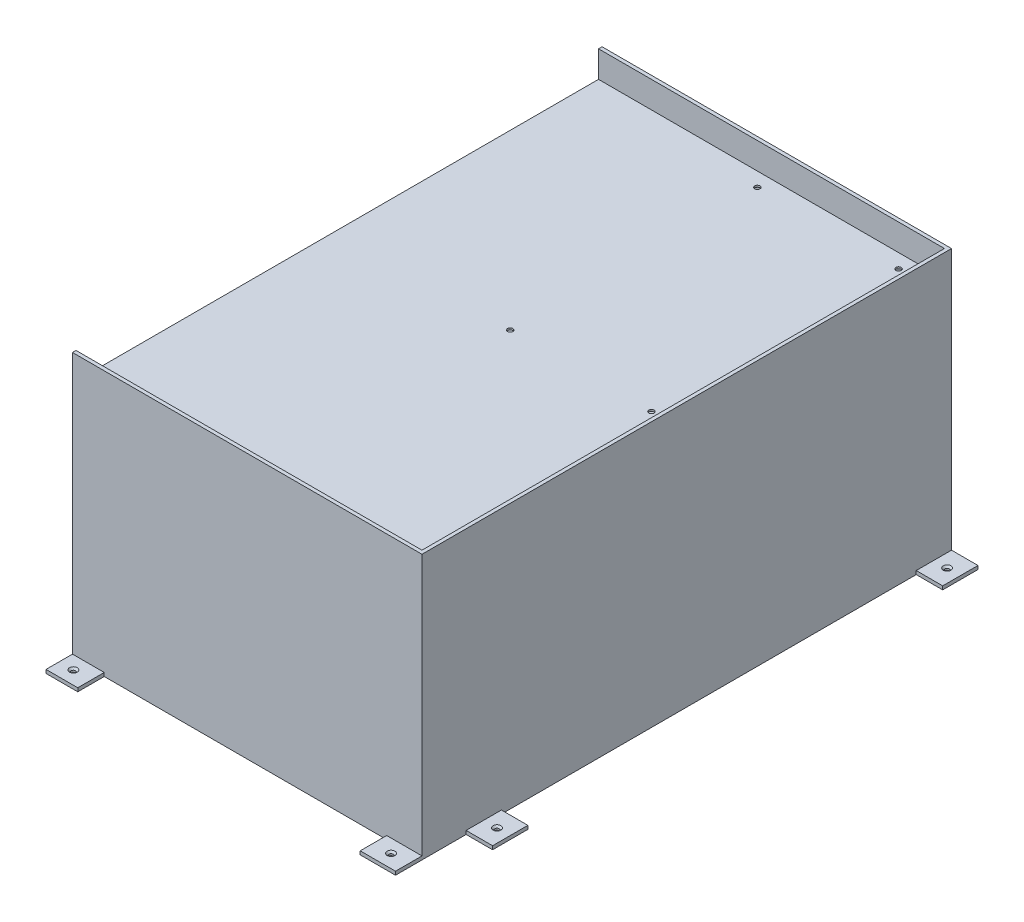
SolidWorks part; units mm, degrees
ref_plane "Front Plane" through (0, 0, 0) normal (0, 0, 1) x (1, 0, 0)
ref_plane "Top Plane" through (0, 0, 0) normal (0, 1, 0) x (1, 0, 0)
ref_plane "Right Plane" through (0, 0, 0) normal (1, 0, 0) x (0, 0, -1)
sketch "Sketch2" plane through (0, 0, 0) normal (0, 1, 0) x (1, 0, 0)
  line L1 (100, -150) -> (-100, -150)
  line L2 (100, -150) -> (100, 150)
  line L3 (100, 150) -> (-100, 150)
  line L4 (-100, -150) -> (-100, 150)
  line L5 (100, -150) -> (-100, 150) construction
  line L6 (100, 150) -> (-100, -150) construction
  point P0 (0, 0)
  dimension "D1" = 300
  dimension "D2" = 200
extrude "Boss-Extrude1" add sketch "Sketch2" along normal blind 150
shell "Shell1" thickness 2
sketch "Sketch4" plane through (0, 0, 0) normal (0, 1, 0) x (1, 0, 0)
  line L0 (-100, -150) -> (100, -150) construction
  line L5 (-100, -150) -> (-80, -150)
  line L6 (-100, -150) -> (-100, -165)
  line L7 (-100, -165) -> (-80, -165)
  line L8 (-80, -150) -> (-80, -165)
  line L9 (100, -150) -> (100, 150) construction
  line L10 (100, -150) -> (80, -150)
  line L11 (100, -150) -> (100, -165)
  line L12 (100, -165) -> (80, -165)
  line L13 (80, -150) -> (80, -165)
  line L14 (100, 150) -> (115, 150)
  line L15 (100, 150) -> (100, 130)
  line L16 (100, 130) -> (115, 130)
  line L17 (115, 150) -> (115, 130)
  line L18 (100, -125) -> (115, -125)
  line L19 (100, -125) -> (100, -105)
  line L20 (100, -105) -> (115, -105)
  line L21 (115, -125) -> (115, -105)
  dimension "D1" = 20
  dimension "D2" = 15
  dimension "D3" = 15
  dimension "D4" = 20
  dimension "D5" = 20
  dimension "D6" = 15
  dimension "D7" = 20
  dimension "D8" = 15
  dimension "D9" = 25
extrude "Boss-Extrude2" add sketch "Sketch4" along normal blind 2
hole_wizard "CSK for M2 Countersunk Flat Head Screw1" positions "3DSketch2" profile "Sketch5" countersink size "M2" standard "ISO"
sketch3d "3DSketch2"
  line L0 (-100, 2, 157.5) -> (100, 2, 157.5) construction
  line L1 (-100, 2, 150) -> (-100, 2, 165) construction
  line L2 (100, 2, 165) -> (100, 2, 150) construction
  point P0 (107.5, 2, -140)
  point P2 (107.5, 2, 115)
  point P4 (90, 2, 157.5)
  point P6 (-90, 2, 157.5)
sketch "Sketch5" plane through (107.5, 2, -140) normal (1, 0, 0) x (0, 0, 1)
  line L0 (0, 0) -> (0, 30.721)
  line L1 (0, 30.721) -> (1.2, 30)
  line L2 (1.2, 30) -> (1.2, 1)
  line L3 (1.2, 1) -> (2.2, 0)
  line L5 (2.2, 0) -> (0, 0)
  line L6 (-1.2, 1) -> (-2.2, 0) construction
  line L10 (0, 30.721) -> (-1.2, 30) construction
  line L11 (0, -6.35) -> (0, 107.95) construction
  dimension "Hole Dia." = 2.4
  dimension "Hole Depth" = 30
  dimension "Near C'Sink Dia." = 4.4
  dimension "Near C'Sink Angle" = 90
  dimension "Drill Angle" = 118
sketch "Sketch6" plane through (0, 0, 148) normal (0, 0, -1) x (-1, 0, 0)
  line L0 (-100, 76) -> (100, 75) construction
  line L1 (-100, 150) -> (-100, 2) construction
  line L3 (100, 150) -> (100, 0) construction
  line L4 (-100, 45) -> (100, 45)
  line L5 (-100, 90) -> (100, 90)
  line L6 (-100, 135) -> (100, 135)
  line L7 (-115, 0) -> (100, 0) construction
  dimension "D1" = 45
  dimension "D2" = 45
  dimension "D3" = 45
extrude "Extrude-Thin1" add sketch "Sketch6" along normal up to vertex (296 mm away) thin
sketch "Sketch7" plane through (-100, 0, 0) normal (-1, 0, 0) x (0, 0, 1)
  line L6 (-150, 0) -> (165, 0)
  line L7 (165, 0) -> (165, 2)
  line L8 (165, 2) -> (150, 2)
  line L9 (150, 2) -> (150, 150)
  line L10 (150, 150) -> (-150, 150)
  line L11 (-150, 150) -> (-150, 0)
  line L12 (-150, 0) -> (165, 0)
  line L13 (165, 0) -> (165, 2)
  line L14 (165, 2) -> (150, 2)
  line L15 (150, 2) -> (150, 150)
  line L16 (150, 150) -> (-150, 150)
  line L17 (-150, 150) -> (-150, 0)
  dimension "D1" = 0
extrude "Cut-Extrude1" cut sketch "Sketch7" against normal up to surface (2 mm away) up to face at (-98, 142.5, 0)
sketch "Sketch8" plane through (0, 135, 0) normal (0, 1, 0) x (1, 0, 0)
  line L1 (0, 0) -> (80, 0)
  line L2 (0, 0) -> (0, 140)
  line L3 (0, 140) -> (80, 140)
  line L4 (80, 0) -> (80, 140)
  point P0 (0, 0)
  point P1 (80, 140)
  point P2 (0, 140)
  point P3 (80, 0)
  dimension "D1" = 140
  dimension "D2" = 80
hole_wizard "Ø3.0mm Dowel Hole1" positions "Sketch8" profile "Sketch9" hole size "Ø3.0" standard "ISO"
sketch "Sketch9" plane through (0, 135, 0) normal (1, 0, 0) x (0, 0, 1)
  line L0 (0, 0) -> (0, 30.9013)
  line L1 (0, 30.9013) -> (1.5, 30)
  line L2 (1.5, 30) -> (1.5, 0)
  line L5 (1.5, 0) -> (0, 0)
  line L10 (0, 30.9013) -> (-1.5, 30) construction
  line L11 (0, -6.35) -> (0, 107.95) construction
  dimension "Hole Dia." = 3
  dimension "Hole Depth" = 30
  dimension "Drill Angle" = 118
